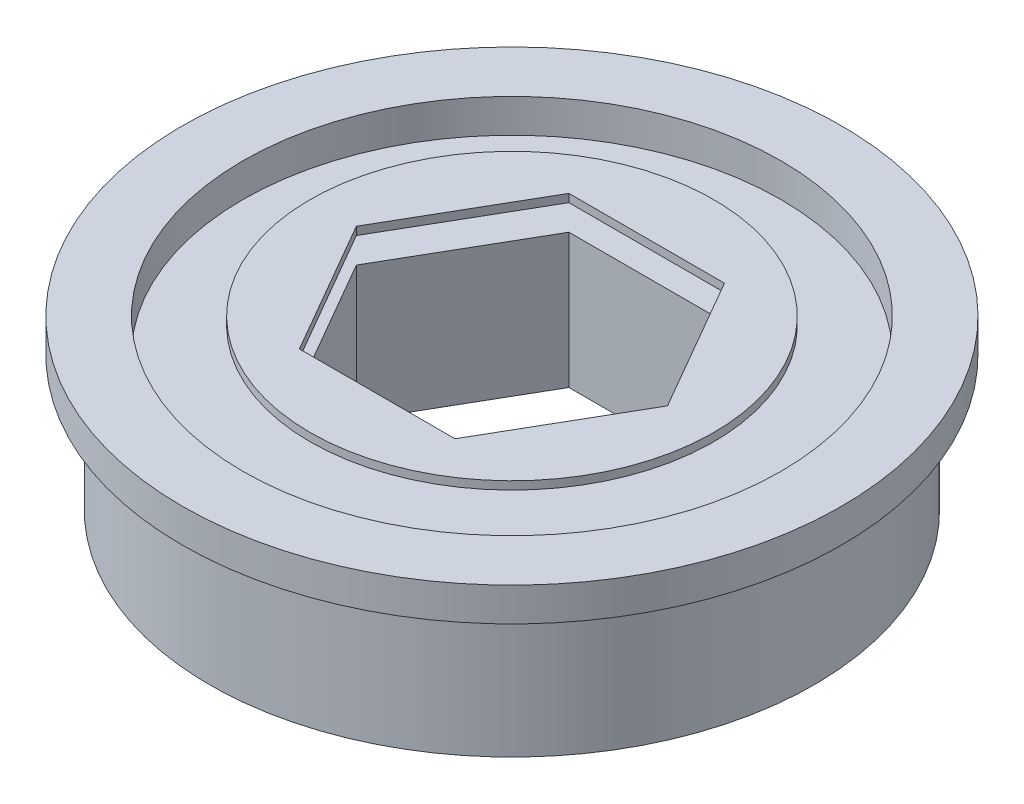
SolidWorks part; units mm, degrees
ref_plane "Front Plane" through (0, 0, 0) normal (0, 0, 1) x (1, 0, 0)
ref_plane "Top Plane" through (0, 0, 0) normal (0, 1, 0) x (1, 0, 0)
ref_plane "Right Plane" through (0, 0, 0) normal (1, 0, 0) x (0, 0, -1)
ref_plane "Plane1" through (0, 0, 0) normal (0, 0, -1) x (-1, 0, 0)
sketch "Sketch1" plane through (0, 0, 0) normal (0, 0, -1) x (-1, 0, 0)
  line L0 (-15.5575, 6.35) -> (0, 6.35)
  line L1 (0, 6.35) -> (0, 7.9375)
  line L2 (0, 7.9375) -> (-15.5575, 7.9375)
  line L3 (-15.5575, 7.9375) -> (-15.5575, 6.35)
  line L4 (0, 6.35) -> (0, 7.9375) construction
revolve "Revolve1" add sketch "Sketch1" angle 360 about L4
hole_wizard "M22 Clearance Hole1" positions "Sketch3" profile "Sketch2" hole size "M22" standard "ANSI Metric"
sketch "Sketch3" plane through (0, 7.9375, 0) normal (0, 1, 0) x (1, 0, 0)
  point P0 (0, 0)
sketch "Sketch2" plane through (0, 7.9375, 0) normal (1, 0, 0) x (0, 0, 1)
  line L0 (0, 0) -> (0, 1.5875)
  line L1 (0, 1.5875) -> (12.7, 1.5875)
  line L2 (12.7, 1.5875) -> (12.7, 0)
  line L5 (12.7, 0) -> (0, 0)
  line L11 (0, -6.35) -> (0, 107.95) construction
  dimension "Thru Hole Dia." = 25.4
  dimension "Thru Hole Depth" = 1.5875
ref_plane "Plane2" through (0, 7.5565, 0) normal (0, -1, 0) x (1, 0, 0)
sketch "Sketch4" plane through (0, 7.5565, 0) normal (0, -1, 0) x (1, 0, 0)
  circle A0 centre (0, 0) radius 9.525
extrude "Boss-Extrude1" add sketch "Sketch4" against normal blind 0.381
sketch "Sketch5" plane through (0, 6.35, 0) normal (0, -1, 0) x (1, 0, 0)
  circle A0 centre (0, 0) radius 14.2748
extrude "Boss-Extrude2" add sketch "Sketch5" along normal blind 6.35
sketch "Sketch6" plane through (0, 0, 0) normal (0, -1, 0) x (1, 0, 0)
  line L0 (-3.6719, 6.36) -> (-7.3439, 0)
  line L1 (-7.3439, 0) -> (-3.6719, -6.36)
  line L2 (-3.6719, -6.36) -> (3.6719, -6.36)
  line L3 (3.6719, -6.36) -> (7.3439, 0)
  line L4 (7.3439, 0) -> (3.6719, 6.36)
  line L5 (3.6719, 6.36) -> (-3.6719, 6.36)
extrude "Cut-Extrude1" cut sketch "Sketch6" against normal through all
